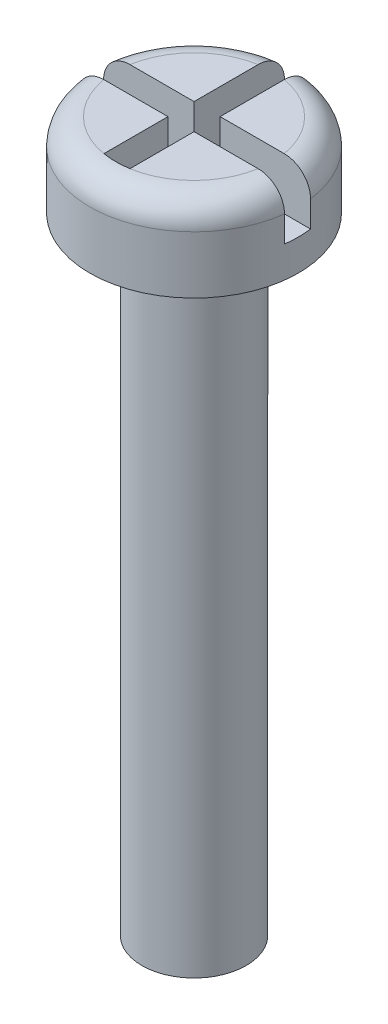
SolidWorks part; units mm, degrees
material "6061 Alloy"
ref_plane "Front Plane" through (0, 0, 0) normal (0, 0, 1) x (1, 0, 0)
ref_plane "Top Plane" through (0, 0, 0) normal (0, 1, 0) x (1, 0, 0)
ref_plane "Right Plane" through (0, 0, 0) normal (1, 0, 0) x (0, 0, -1)
sketch "Sketch1" plane through (0, 0, 0) normal (0, 1, 0) x (1, 0, 0)
  circle A0 centre (0, 0) radius 2
  dimension "D1" = 4
extrude "Boss-Extrude1" add sketch "Sketch1" along normal blind 1.6
fillet "Fillet1" radius 0.5 1 edges at (0, 1.6, 2)
sketch "Sketch2" plane through (0, 0, 0) normal (0, -1, 0) x (1, 0, 0)
  circle A0 centre (0, 0) radius 1
extrude "Boss-Extrude2" add sketch "Sketch2" along normal blind 12
sketch "Sketch3" plane through (0, 1.6, 0) normal (0, 1, 0) x (1, 0, 0)
  line L0 (0, 2) -> (0, -0.25) construction
  line L1 (-0.25, 0) -> (0.25, 0) construction
  line L2 (-0.25, 2) -> (-0.25, 0.25)
  line L3 (-2, -0.25) -> (-0.25, -0.25)
  line L4 (0.25, 2) -> (0.25, 0.25)
  line L5 (-2, 0.25) -> (-0.25, 0.25)
  line L6 (-0.25, 2) -> (0.25, 2)
  line L7 (2, 0.25) -> (2, -0.25)
  line L8 (2, -0.25) -> (2.0205, -0.2459)
  line L9 (-0.25, -2) -> (0.25, -2)
  line L10 (-2, 0.25) -> (-2, -0.25)
  line L11 (0.25, 0.25) -> (2, 0.25)
  line L12 (-2, 0.25) -> (2, 0.25) construction
  line L13 (-0.25, -0.25) -> (-0.25, -2)
  line L14 (-0.25, 2) -> (-0.25, -2) construction
  line L15 (-2, 0) -> (2, 0) construction
  line L16 (0.25, -0.25) -> (2, -0.25)
  line L17 (-2, -0.25) -> (2, -0.25) construction
  line L18 (0, 2) -> (0, -2) construction
  line L19 (0.25, -0.25) -> (0.25, -2)
  line L20 (0.25, 2) -> (0.25, -2) construction
  circle A0 centre (0, 0) radius 2 construction
  circle M1 centre (0, 0) radius 1.5
  dimension "D1" = 0.25
  dimension "D2" = 0.25
extrude "Cut-Extrude1" cut sketch "Sketch3" against normal blind 1 contours L19 L16 L11 L4 L2 L5 L3 L13 M1 | L16 L7 L11 M1 | L5 L10 L3 M1 | L6 L2 L4 M1
